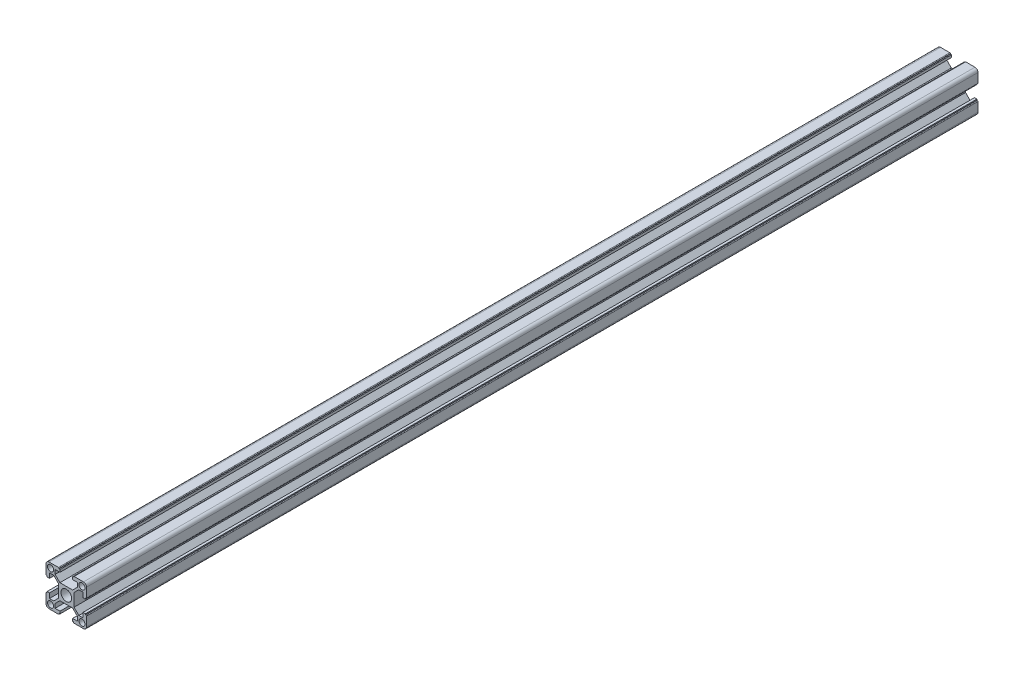
SolidWorks part; units mm, degrees
ref_plane "前视基准面" through (0, 0, 0) normal (0, 0, 1) x (1, 0, 0)
ref_plane "上视基准面" through (0, 0, 0) normal (0, 1, 0) x (1, 0, 0)
ref_plane "右视基准面" through (0, 0, 0) normal (1, 0, 0) x (0, 0, -1)
sketch "草图1" plane through (0, 0, 0) normal (0, 0, 1) x (1, 0, 0)
  line L0 (-7.75, 0) -> (0, 0) construction
  line L1 (7.75, -7.75) -> (-7.75, -7.75) construction
  line L2 (7.75, -7.75) -> (7.75, 7.75) construction
  line L3 (7.75, 7.75) -> (-7.75, 7.75) construction
  line L4 (-7.75, -7.75) -> (-7.75, 7.75) construction
  line L5 (7.75, -7.75) -> (-7.75, 7.75) construction
  line L6 (7.75, 7.75) -> (-7.75, -7.75) construction
  line L7 (0, 0) -> (0, 7.75) construction
  line L8 (3.1429, 3.85) -> (-3.1429, 3.85)
  line L9 (-3.1429, 3.85) -> (-5.5, 6.2071)
  line L10 (-5.5, 6.2071) -> (-5.5, 8.3)
  line L11 (-5.5, 8.3) -> (-3.1, 8.3)
  line L12 (-3.1, 8.3) -> (-3.1, 9.5)
  line L13 (-3.1, 9.5) -> (-3.6, 9.5)
  line L14 (-3.6, 9.5) -> (-3.6, 9.7)
  line L15 (-3.9, 10) -> (-8.5, 10)
  line L16 (-3.85, -3.1429) -> (-3.85, 3.1429)
  line L17 (-3.85, 3.1429) -> (-6.2071, 5.5)
  line L18 (-6.2071, 5.5) -> (-8.3, 5.5)
  line L19 (-8.3, 5.5) -> (-8.3, 3.1)
  line L20 (-9.5, 3.1) -> (-9.5, 3.6)
  line L21 (-8.3, 3.1) -> (-9.5, 3.1)
  line L22 (-9.5, 3.6) -> (-9.7, 3.6)
  line L23 (-10, 3.9) -> (-10, 8.5)
  line L24 (5.5, 8.3) -> (3.1, 8.3)
  line L25 (3.6, 9.5) -> (3.6, 9.7)
  line L26 (3.1, 9.5) -> (3.6, 9.5)
  line L27 (3.1, 8.3) -> (3.1, 9.5)
  line L28 (5.5, 6.2071) -> (5.5, 8.3)
  line L29 (3.1429, 3.85) -> (5.5, 6.2071)
  line L30 (3.85, -3.1429) -> (3.85, 3.1429)
  line L31 (3.85, 3.1429) -> (6.2071, 5.5)
  line L32 (9.5, 3.6) -> (9.7, 3.6)
  line L33 (8.3, 3.1) -> (9.5, 3.1)
  line L34 (9.5, 3.1) -> (9.5, 3.6)
  line L35 (8.3, 5.5) -> (8.3, 3.1)
  line L36 (6.2071, 5.5) -> (8.3, 5.5)
  line L37 (10, 3.9) -> (10, 8.5)
  line L38 (3.9, 10) -> (8.5, 10)
  line L39 (-9.5, -3.6) -> (-9.7, -3.6)
  line L40 (-8.3, -3.1) -> (-9.5, -3.1)
  line L41 (-9.5, -3.1) -> (-9.5, -3.6)
  line L42 (-8.3, -5.5) -> (-8.3, -3.1)
  line L43 (-6.2071, -5.5) -> (-8.3, -5.5)
  line L44 (-3.85, -3.1429) -> (-6.2071, -5.5)
  line L45 (-3.1429, -3.85) -> (-5.5, -6.2071)
  line L46 (-5.5, -6.2071) -> (-5.5, -8.3)
  line L47 (-3.6, -9.5) -> (-3.6, -9.7)
  line L48 (-3.1, -9.5) -> (-3.6, -9.5)
  line L49 (-3.1, -8.3) -> (-3.1, -9.5)
  line L50 (-5.5, -8.3) -> (-3.1, -8.3)
  line L51 (5.5, -6.2071) -> (5.5, -8.3)
  line L52 (3.1, -8.3) -> (3.1, -9.5)
  line L53 (3.1, -9.5) -> (3.6, -9.5)
  line L54 (3.6, -9.5) -> (3.6, -9.7)
  line L55 (5.5, -8.3) -> (3.1, -8.3)
  line L56 (3.1429, -3.85) -> (5.5, -6.2071)
  line L57 (3.1429, -3.85) -> (-3.1429, -3.85)
  line L58 (3.85, -3.1429) -> (6.2071, -5.5)
  line L59 (6.2071, -5.5) -> (8.3, -5.5)
  line L60 (8.3, -5.5) -> (8.3, -3.1)
  line L61 (9.5, -3.1) -> (9.5, -3.6)
  line L62 (8.3, -3.1) -> (9.5, -3.1)
  line L63 (9.5, -3.6) -> (9.7, -3.6)
  line L64 (3.9, -10) -> (8.5, -10)
  line L65 (10, -3.9) -> (10, -8.5)
  line L66 (-10, -3.9) -> (-10, -8.5)
  line L67 (-3.9, -10) -> (-8.5, -10)
  circle A0 centre (0, 0) radius 2.65
  circle A1 centre (-7.75, 7.75) radius 1.5
  circle A2 centre (7.75, 7.75) radius 1.5
  circle A3 centre (7.75, -7.75) radius 1.5
  circle A4 centre (-7.75, -7.75) radius 1.5
  arc A5 (-10, -8.5) -> (-8.5, -10) centre (-8.5, -8.5) ccw
  arc A6 (8.5, -10) -> (10, -8.5) centre (8.5, -8.5) ccw
  arc A7 (10, 8.5) -> (8.5, 10) centre (8.5, 8.5) ccw
  arc A8 (-8.5, 10) -> (-10, 8.5) centre (-8.5, 8.5) ccw
  arc A9 (3.6, -9.7) -> (3.9, -10) centre (3.9, -9.7) ccw
  arc A10 (-3.6, -9.7) -> (-3.9, -10) centre (-3.9, -9.7) cw
  arc A11 (-9.7, -3.6) -> (-10, -3.9) centre (-9.7, -3.9) ccw
  arc A12 (9.7, -3.6) -> (10, -3.9) centre (9.7, -3.9) cw
  arc A13 (9.7, 3.6) -> (10, 3.9) centre (9.7, 3.9) ccw
  arc A14 (-9.7, 3.6) -> (-10, 3.9) centre (-9.7, 3.9) cw
  arc A15 (3.6, 9.7) -> (3.9, 10) centre (3.9, 9.7) cw
  arc A16 (-3.6, 9.7) -> (-3.9, 10) centre (-3.9, 9.7) ccw
  point P46 (0, 3.85)
  point P56 (-3.85, 0)
  point P78 (3.85, 0)
  point P87 (-10, -10)
  point P90 (10, -10)
  point P93 (10, 10)
  point P96 (-10, 10)
  point P99 (3.6, -10)
  point P102 (-3.6, -10)
  point P105 (-10, -3.6)
  point P108 (10, -3.6)
  point P111 (10, 3.6)
  point P114 (-10, 3.6)
  point P117 (3.6, 10)
  point P120 (-3.6, 10)
  dimension "D1" = 5.3
  dimension "D2" = 3
  dimension "D11" = 1.5
  dimension "D12" = 2.25
  dimension "D13" = 0.3
  dimension "D3" = 7.7
  dimension "D4" = 6.2
  dimension "D5" = 1.7
  dimension "D6" = 1.2
  dimension "D7" = 20
  dimension "D8" = 7.2
  dimension "D9" = 11
  dimension "D10" = 1
extrude "凸台-拉伸1" add sketch "草图1" along normal mid plane 440
sketch "草图4" plane through (3.85, 0, 0) normal (1, 0, 0) x (0, 0, -1)
  line L0 (210, 0) -> (-210, 0) construction
  line L1 (-220, -3.1429) -> (-220, 3.1429) construction
  circle A0 centre (-210, 0) radius 2
  circle A1 centre (210, 0) radius 2
  circle A2 centre (-190, 0) radius 2
  circle A3 centre (190, 0) radius 2
  circle A4 centre (-100, 0) radius 2
  circle A5 centre (100, 0) radius 2
  point P4 (0, 0)
  dimension "D1" = 4
  dimension "D2" = 10
  dimension "D3" = 20
  dimension "D4" = 20
  dimension "D5" = 100
  dimension "D6" = 100
extrude "切除-拉伸3" cut sketch "草图4" against normal through all
equation "\"D4@草图4\"=\"D3@草图4\""
equation "\"D6@草图4\"=\"D5@草图4\""
